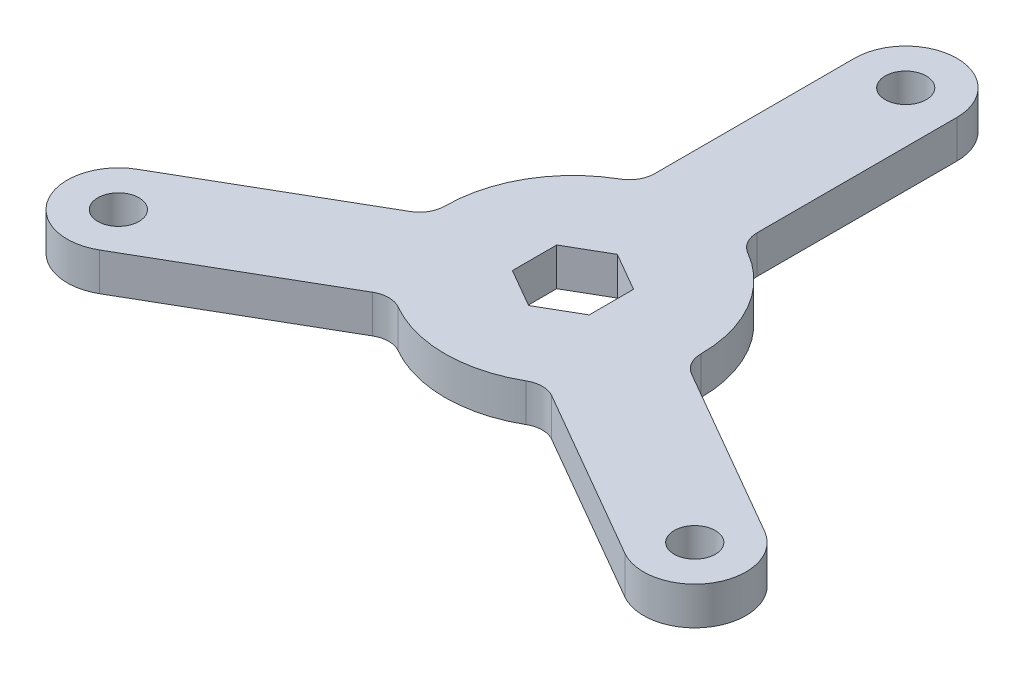
SolidWorks part; units mm, degrees
ref_plane "Front Plane" through (0, 0, 0) normal (0, 0, 1) x (1, 0, 0)
ref_plane "Top Plane" through (0, 0, 0) normal (0, 1, 0) x (1, 0, 0)
ref_plane "Right Plane" through (0, 0, 0) normal (1, 0, 0) x (0, 0, -1)
sketch "Sketch1" plane through (0, 0, 0) normal (0, 1, 0) x (1, 0, 0)
  line L1 (0, 5.4993) -> (-4.7625, 2.7496)
  line L2 (-4.7625, 2.7496) -> (-4.7625, -2.7496)
  line L3 (-4.7625, -2.7496) -> (0, -5.4993)
  line L4 (0, -5.4993) -> (4.7625, -2.7496)
  line L5 (4.7625, -2.7496) -> (4.7625, 2.7496)
  line L6 (4.7625, 2.7496) -> (0, 5.4993)
  circle A0 centre (0, 0) radius 15.875
  circle A1 centre (0, 0) radius 4.7625 construction
  dimension "D1" = 31.75
  dimension "D2" = 9.525
extrude "Boss-Extrude1" add sketch "Sketch1" along normal mid plane 4.699
sketch "Sketch2" plane through (0, 2.3495, 0) normal (0, 1, 0) x (1, 0, 0)
  line L0 (0, 15.875) -> (0, 41.275) construction
  line L1 (-6.35, 41.275) -> (-6.35, 14.5497)
  line L3 (6.35, 14.5497) -> (6.35, 41.275)
  circle A0 centre (0, 0) radius 15.875 construction
  circle A1 centre (0, 41.275) radius 2.5527
  arc A2 (6.35, 41.275) -> (-6.35, 41.275) centre (0, 41.275) ccw
  arc A3 (-6.35, 14.5497) -> (6.35, 14.5497) centre (0, 0) cw
  dimension "D1" = 12.7
  dimension "D2" = 5.1054
  dimension "D3" = 25.4
extrude "Boss-Extrude2" add sketch "Sketch2" against normal up to surface (4.699 mm away) up to face at (0, -2.3495, 15.875)
fillet "Fillet1" radius 3.175 2 edges at (6.35, 0, -14.5497) (-6.35, 0, -14.5497)
pattern_circular "CirPattern1" count 3 over 360 about axis through (0, 0, 0) along (0, 1, 0) of "Fillet1", "Boss-Extrude2"
